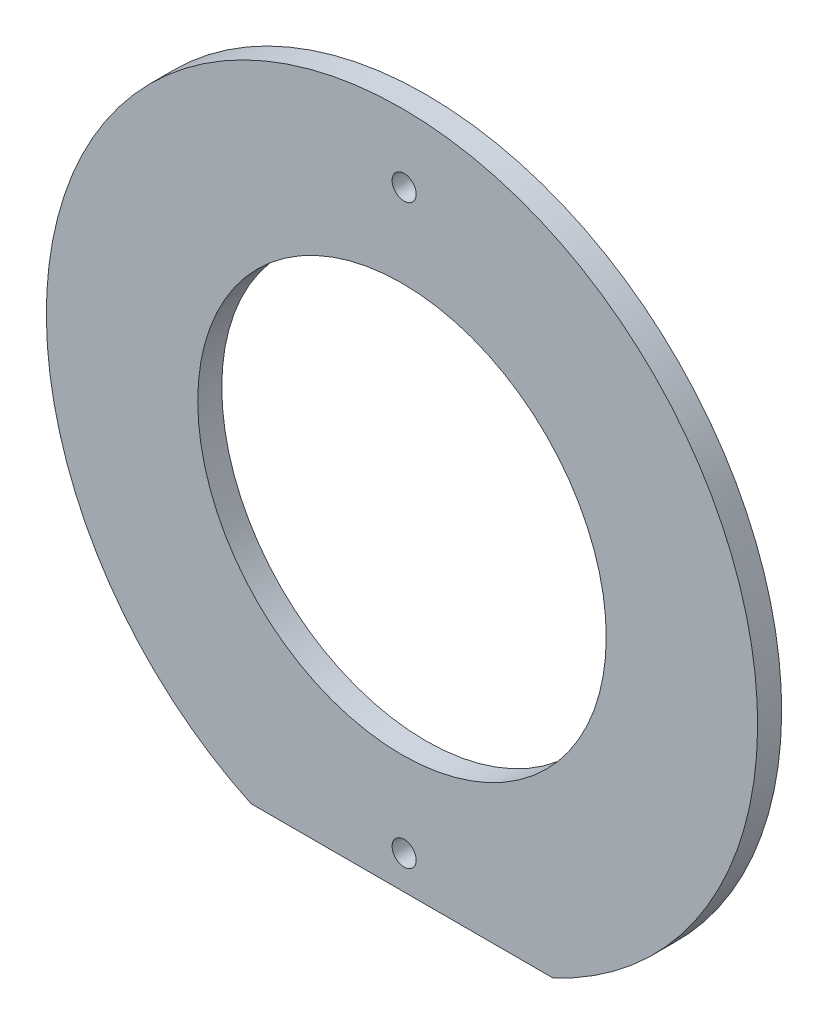
SolidWorks part; units mm, degrees
ref_plane "Front Plane" through (0, 0, 0) normal (0, 0, 1) x (1, 0, 0)
ref_plane "Top Plane" through (0, 0, 0) normal (0, 1, 0) x (1, 0, 0)
ref_plane "Right Plane" through (0, 0, 0) normal (1, 0, 0) x (0, 0, -1)
sketch "Sketch1" plane through (0, 0, 0) normal (0, 0, 1) x (1, 0, 0)
  line L3 (-125.8136, 5.5024) -> (-62.9805, 5.5024)
  arc A0 (-62.9805, 5.5024) -> (-125.8136, 5.5024) centre (-94.397, 72.5024) ccw
  dimension "D1" = 148
extrude "Boss-Extrude1" add sketch "Sketch1" along normal blind 5
sketch "Sketch2" plane through (0, 0, 5) normal (0, 0, 1) x (1, 0, 0)
  circle A0 centre (-93.9534, 132.5024) radius 2.5
  circle A1 centre (-94.397, 72.5024) radius 74 construction
  circle A2 centre (-93.9534, 12.5024) radius 2.5
  dimension "D1" = 5
  dimension "D3" = 60
  dimension "D2" = 60
extrude "Cut-Extrude1" cut sketch "Sketch2" against normal blind 10
sketch "Sketch3" plane through (0, 0, 5) normal (0, 0, 1) x (1, 0, 0)
  arc A0 (-62.9805, 5.5024) -> (-125.8136, 5.5024) centre (-94.397, 72.5024) ccw construction
  arc A1 (-62.9805, 5.5024) -> (-125.8136, 5.5024) centre (-94.397, 72.5024) ccw construction
  circle A2 centre (-94.397, 72.5024) radius 42.5
  dimension "D1" = 85
extrude "Cut-Extrude2" cut sketch "Sketch3" against normal up to next
